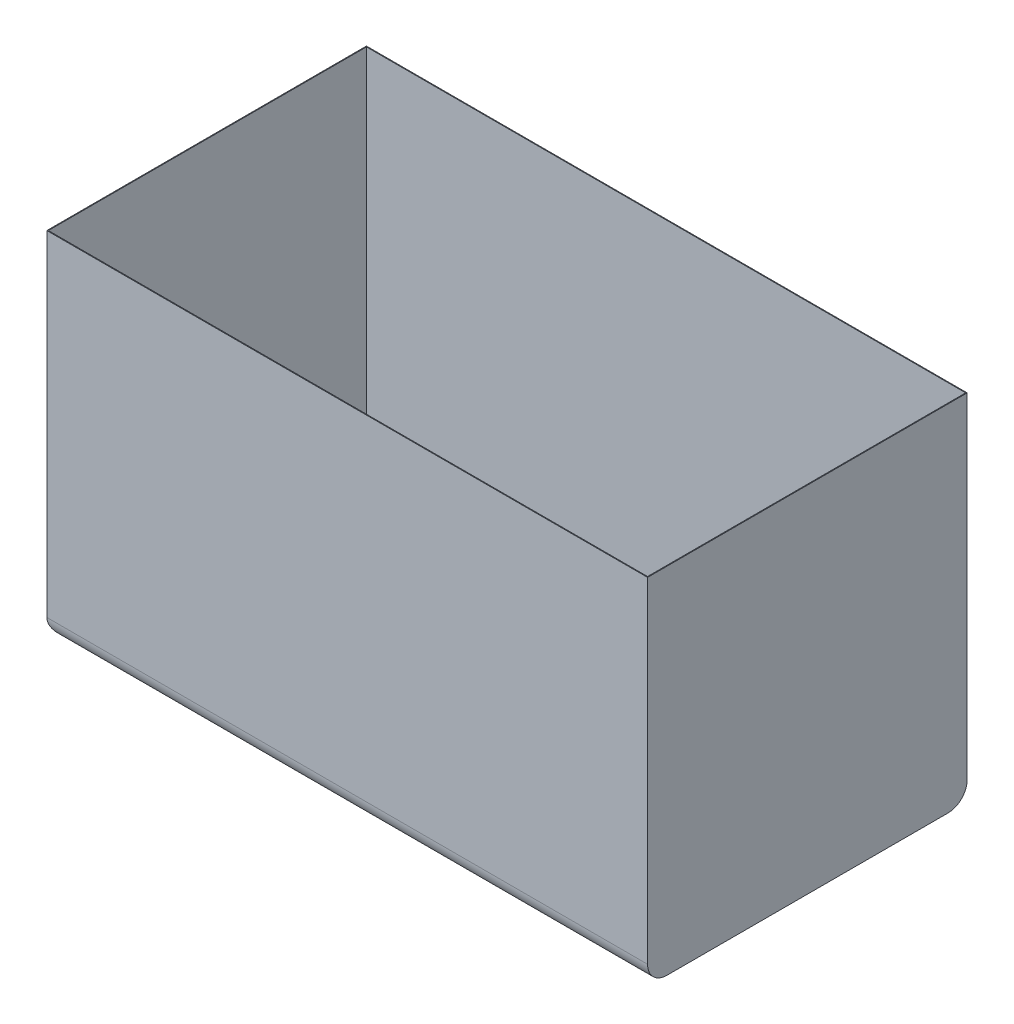
SolidWorks part; units mm, degrees
ref_plane "Front Plane" through (0, 0, 0) normal (0, 0, 1) x (1, 0, 0)
ref_plane "Top Plane" through (0, 0, 0) normal (0, 1, 0) x (1, 0, 0)
ref_plane "Right Plane" through (0, 0, 0) normal (1, 0, 0) x (0, 0, -1)
sketch "Sketch1" plane through (0, 0, 0) normal (0, 1, 0) x (1, 0, 0)
  line L1 (0, 0) -> (780, 0)
  line L2 (0, 0) -> (0, -415)
  line L3 (0, -415) -> (780, -415)
  line L4 (780, 0) -> (780, -415)
  dimension "D1" = 780
  dimension "D2" = 415
extrude "Boss-Extrude1" add sketch "Sketch1" along normal blind 460
fillet "Fillet1" radius 25 3 edges at (390, 0, 0) (0, 0, 207.5) (390, 0, 415)
shell "Shell1" thickness 1
sketch "Sketch2" plane through (0, 0, 0) normal (0, -1, 0) x (1, 0, 0)
  line L0 (65, 180) -> (65, 400) construction
  line L1 (1, 414) -> (779, 414) construction
  circle A0 centre (65, 164) radius 3.175
  circle A1 centre (152, 164) radius 3.175
  circle A2 centre (239, 164) radius 3.175
  circle A3 centre (326, 164) radius 3.175
  circle A4 centre (413, 164) radius 3.175
  circle A5 centre (500, 164) radius 3.175
  circle A6 centre (587, 164) radius 3.175
  circle A7 centre (674, 164) radius 3.175
  dimension "D2" = 6.35
  dimension "D3" = 250
  dimension "D1" = 8
extrude "Cut-Extrude2" cut sketch "Sketch2" against normal up to next
